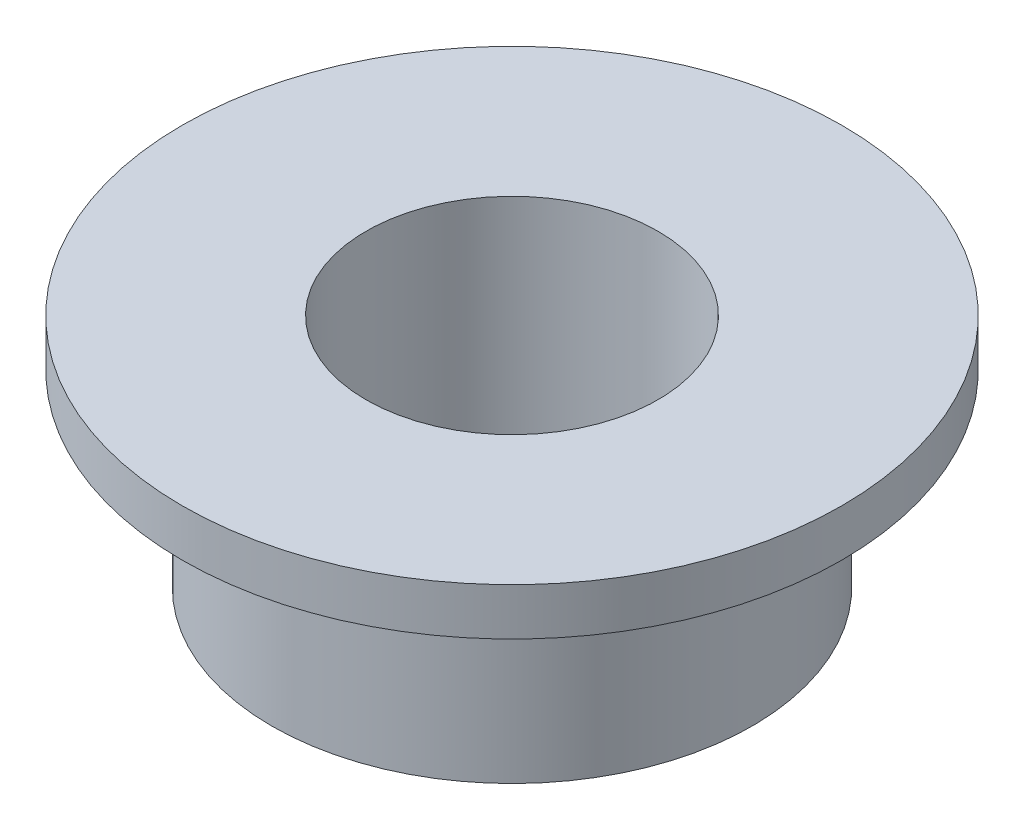
SolidWorks part; units mm, degrees
ref_plane "Front Plane" through (0, 0, 0) normal (0, 0, 1) x (1, 0, 0)
ref_plane "Top Plane" through (0, 0, 0) normal (0, 1, 0) x (1, 0, 0)
ref_plane "Right Plane" through (0, 0, 0) normal (1, 0, 0) x (0, 0, -1)
sketch "Sketch1" plane through (0, 0, 0) normal (0, 1, 0) x (1, 0, 0)
  circle A0 centre (0, 0) radius 7.75
  circle A1 centre (0, 0) radius 12.75
  dimension "D1" = 15.5
  dimension "D2" = 25.5
extrude "Boss-Extrude1" add sketch "Sketch1" along normal mid plane 10
sketch "Sketch2" plane through (0, 5, 0) normal (0, 1, 0) x (1, 0, 0)
  circle A0 centre (0, 0) radius 17.5
  circle A1 centre (0, 0) radius 7.75 construction
  circle A2 centre (0, 0) radius 7.75
  dimension "D1" = 35
extrude "Boss-Extrude2" add sketch "Sketch2" along normal blind 2.5
